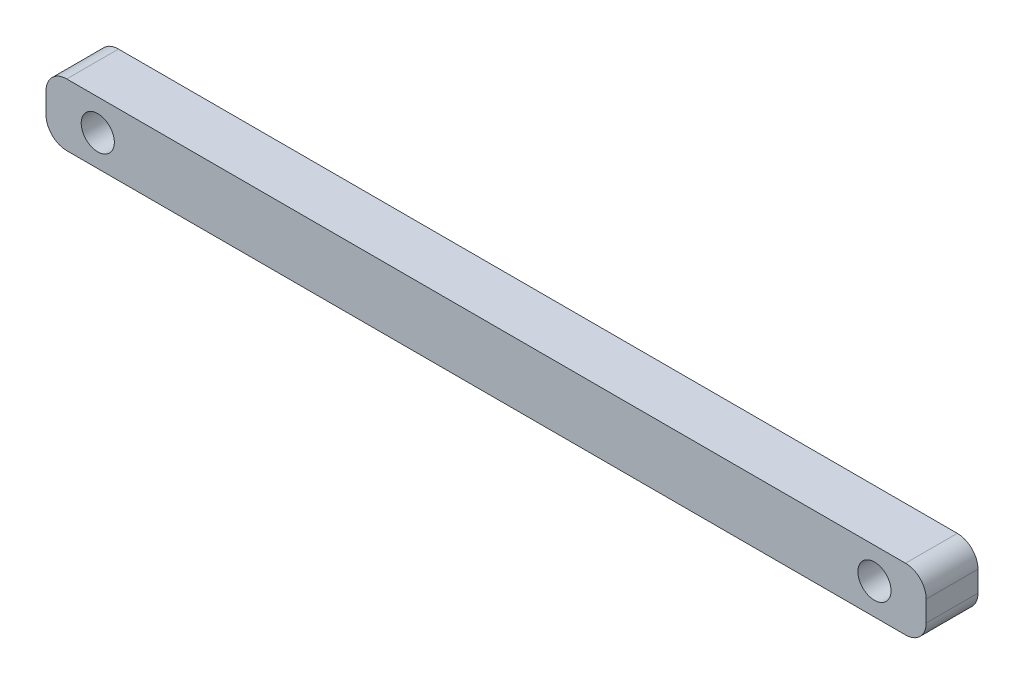
SolidWorks part; units mm, degrees
ref_plane "Front Plane" through (0, 0, 0) normal (0, 0, 1) x (1, 0, 0)
ref_plane "Top Plane" through (0, 0, 0) normal (0, 1, 0) x (1, 0, 0)
ref_plane "Right Plane" through (0, 0, 0) normal (1, 0, 0) x (0, 0, -1)
sketch "Sketch1" plane through (0, 0, 0) normal (0, 0, 1) x (1, 0, 0)
  line L2 (-40.5, 3) -> (40.5, 3)
  line L3 (-42.5, 1) -> (-42.5, -1)
  line L4 (-40.5, -3) -> (40.5, -3)
  line L5 (42.5, 1) -> (42.5, -1)
  line L6 (-42.5, 3) -> (42.5, -3) construction
  line L7 (-42.5, -3) -> (42.5, 3) construction
  circle A0 centre (-37.5, 0) radius 1.6
  circle A1 centre (37.5, 0) radius 1.6
  arc A2 (40.5, -3) -> (42.5, -1) centre (40.5, -1) ccw
  arc A3 (40.5, 3) -> (42.5, 1) centre (40.5, 1) cw
  arc A4 (-42.5, -1) -> (-40.5, -3) centre (-40.5, -1) ccw
  arc A5 (-40.5, 3) -> (-42.5, 1) centre (-40.5, 1) ccw
  point P2 (0, 0)
  dimension "D3" = 3.2
  dimension "D5" = 3.2
  dimension "D7" = 2
  dimension "D1" = 85
  dimension "D2" = 6
  dimension "D4" = 5
  dimension "D6" = 5
extrude "Boss-Extrude1" add sketch "Sketch1" along normal blind 5
